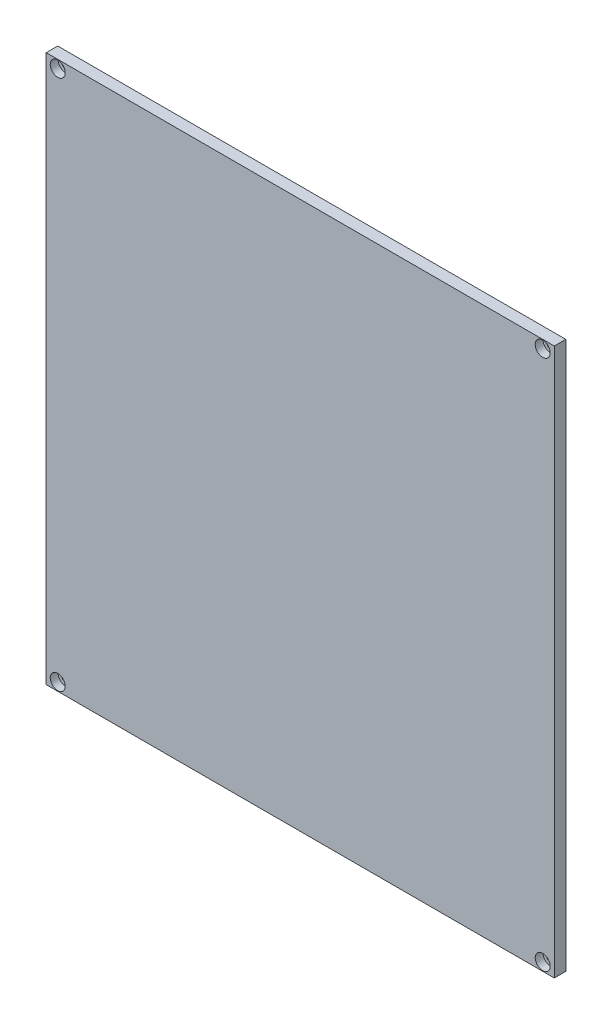
SolidWorks part; units mm, degrees
ref_plane "Płaszczyzna przednia" through (0, 0, 0) normal (0, 0, 1) x (1, 0, 0)
ref_plane "Płaszczyzna górna" through (0, 0, 0) normal (0, 1, 0) x (1, 0, 0)
ref_plane "Płaszczyzna prawa" through (0, 0, 0) normal (1, 0, 0) x (0, 0, -1)
sketch "Szkic1" plane through (0, 0, 0) normal (0, 0, 1) x (1, 0, 0)
  line L1 (-110, -118.5) -> (110, -118.5)
  line L2 (-110, -118.5) -> (-110, 118.5)
  line L3 (-110, 118.5) -> (110, 118.5)
  line L4 (110, -118.5) -> (110, 118.5)
  line L5 (0, 118.5) -> (0, -118.5) construction
  line L6 (-110, 0) -> (110, 0) construction
  point P0 (0, 0)
  dimension "D1" = 220
  dimension "D2" = 237
extrude "Dodanie-wyciągnięcie1" add sketch "Szkic1" along normal blind 5
sketch "Szkic2" plane through (0, 0, 5) normal (0, 0, 1) x (1, 0, 0)
  line L0 (-110, 118.5) -> (-110, 111.5) construction
  line L1 (-110, 111.5) -> (-100, 111.5) construction
  line L2 (-100, 111.5) -> (-100, 118.5) construction
  line L3 (-100, 118.5) -> (-110, 118.5) construction
  line L4 (-110, -111.5) -> (-110, -118.5) construction
  line L5 (-110, -118.5) -> (-100, -118.5) construction
  line L6 (-100, -118.5) -> (-100, -111.5) construction
  line L7 (-100, -111.5) -> (-110, -111.5) construction
  line L8 (-110, 118.5) -> (-110, 111.5) construction
  line L9 (-110, 111.5) -> (-100, 111.5) construction
  line L10 (-100, 111.5) -> (-100, 118.5) construction
  line L11 (-100, 118.5) -> (-110, 118.5) construction
  line L12 (-110, -111.5) -> (-110, -118.5) construction
  line L13 (-110, -118.5) -> (-100, -118.5) construction
  line L14 (-100, -118.5) -> (-100, -111.5) construction
  line L15 (-100, -111.5) -> (-110, -111.5) construction
  line L16 (-100, 111.5) -> (-110, 118.5) construction
  line L17 (-100, -118.5) -> (-110, -111.5) construction
  point P0 (105, -115)
  point P1 (105, 115)
  point P10 (-105, 115)
  point P13 (-105, -115)
hole_wizard "Pogłębienie walcowe pod M3 Wkręt z łbem walcowym z gniazdem1" positions "Szkic2" profile "Szkic5" counterbore size "M3" standard "DIN"
sketch "Szkic5" plane through (105, -115, 5) normal (1, 0, 0) x (0, -1, 0)
  line L0 (0, 0) -> (0, 7.7815)
  line L1 (0, 7.7815) -> (1.8, 6.7)
  line L2 (1.8, 6.7) -> (1.8, 3.4)
  line L3 (1.8, 3.4) -> (3.25, 3.4)
  line L4 (3.25, 3.4) -> (3.25, 0)
  line L5 (3.25, 0) -> (0, 0)
  line L10 (0, 7.7815) -> (-1.8, 6.7) construction
  line L11 (0, -6.35) -> (0, 107.95) construction
  dimension "Średnica otworu" = 3.6
  dimension "Głębokość otworu" = 6.7
  dimension "Średnica pogłębienia walcowego" = 6.5
  dimension "Głębokość pogłębienia walcowego" = 3.4
  dimension "Kąt wiertła" = 118
